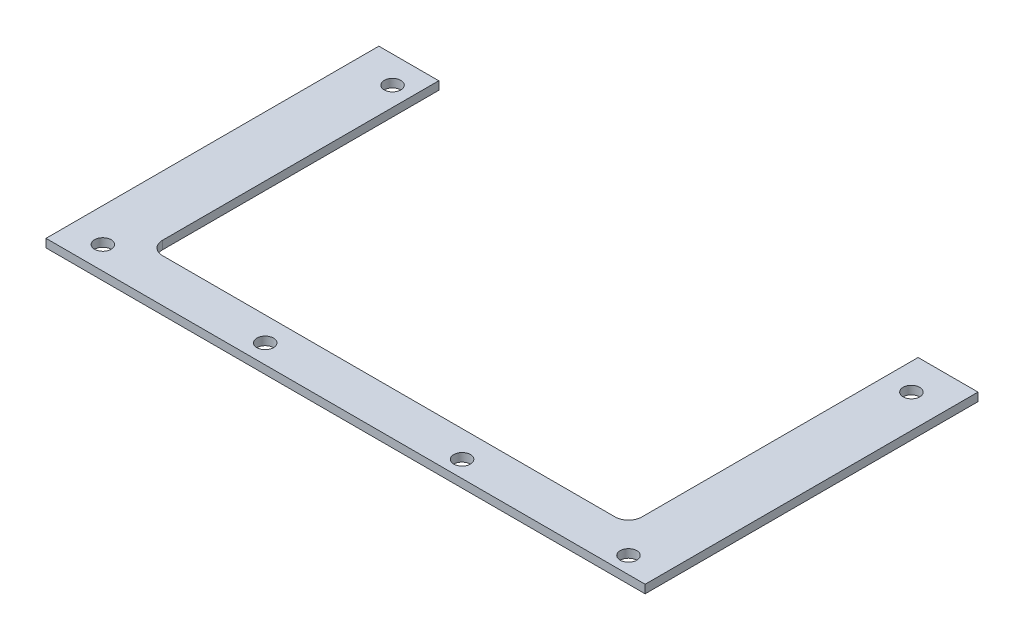
SolidWorks part; units mm, degrees
ref_plane "Front Plane" through (0, 0, 0) normal (0, 0, 1) x (1, 0, 0)
ref_plane "Top Plane" through (0, 0, 0) normal (0, 1, 0) x (1, 0, 0)
ref_plane "Right Plane" through (0, 0, 0) normal (1, 0, 0) x (0, 0, -1)
sketch "Sketch1" plane through (0, 25.4, 0) normal (0, 1, 0) x (1, 0, 0)
  line L0 (-86.36, 311.15) -> (86.36, 311.15)
  line L1 (-101.6, 342.9) -> (101.6, 342.9)
  line L2 (-101.6, 342.9) -> (-101.6, 215.9)
  line L3 (-101.6, 215.9) -> (101.6, 215.9)
  line L4 (101.6, 342.9) -> (101.6, 215.9)
  line L5 (-86.36, 234.95) -> (86.36, 234.95)
  line L6 (-88.9, 237.49) -> (-88.9, 308.61)
  line L7 (88.9, 308.61) -> (88.9, 237.49)
  line L8 (88.9, 308.61) -> (88.9, 237.49)
  line L9 (-88.9, 237.49) -> (-88.9, 308.61)
  line L10 (-86.36, 234.95) -> (86.36, 234.95)
  line L11 (-86.36, 311.15) -> (86.36, 311.15)
  line L13 (91.44, 342.9) -> (91.44, 237.49)
  line L14 (-86.36, 232.41) -> (86.36, 232.41)
  line L15 (-91.44, 237.49) -> (-91.44, 342.9)
  line L16 (-86.36, 313.69) -> (86.36, 313.69)
  line L17 (91.44, 308.61) -> (91.44, 237.49) construction
  line L18 (-91.44, 237.49) -> (-91.44, 308.61) construction
  line L20 (101.6, 215.9) -> (114.3, 215.9)
  line L21 (101.6, 215.9) -> (101.6, 342.9)
  line L22 (101.6, 342.9) -> (114.3, 342.9)
  line L23 (114.3, 215.9) -> (114.3, 342.9)
  line L24 (-114.3, 215.9) -> (-101.6, 215.9)
  line L25 (-114.3, 215.9) -> (-114.3, 342.9)
  line L26 (-114.3, 342.9) -> (-101.6, 342.9)
  line L27 (-101.6, 215.9) -> (-101.6, 342.9)
  arc A2 (98.425, 215.9) -> (104.775, 215.9) centre (101.6, 215.9) ccw construction
  arc A3 (98.425, 215.9) -> (104.775, 215.9) centre (101.6, 215.9) ccw
  arc A4 (-88.9, 237.49) -> (-86.36, 234.95) centre (-86.36, 237.49) ccw
  arc A5 (88.9, 308.61) -> (86.36, 311.15) centre (86.36, 308.61) ccw
  arc A6 (-86.36, 311.15) -> (-88.9, 308.61) centre (-86.36, 308.61) ccw
  arc A7 (86.36, 234.95) -> (88.9, 237.49) centre (86.36, 237.49) ccw
  arc A8 (86.36, 234.95) -> (88.9, 237.49) centre (86.36, 237.49) ccw
  arc A9 (-86.36, 311.15) -> (-88.9, 308.61) centre (-86.36, 308.61) ccw
  arc A10 (88.9, 308.61) -> (86.36, 311.15) centre (86.36, 308.61) ccw
  arc A11 (-88.9, 237.49) -> (-86.36, 234.95) centre (-86.36, 237.49) ccw
  arc A12 (86.36, 232.41) -> (91.44, 237.49) centre (86.36, 237.49) ccw
  arc A13 (-91.44, 237.49) -> (-86.36, 232.41) centre (-86.36, 237.49) ccw
  arc A14 (-86.36, 313.69) -> (-91.44, 308.61) centre (-86.36, 308.61) ccw
  arc A15 (91.44, 308.61) -> (86.36, 313.69) centre (86.36, 308.61) ccw
  arc A16 (114.3, 339.725) -> (117.475, 342.9) centre (114.3, 342.9) ccw construction
  arc A17 (114.3, 339.725) -> (117.475, 342.9) centre (114.3, 342.9) ccw
  arc A18 (-114.3, 219.075) -> (-111.125, 215.9) centre (-114.3, 215.9) ccw construction
  arc A19 (-114.3, 219.075) -> (-111.125, 215.9) centre (-114.3, 215.9) ccw
  dimension "D1" = 2.54
extrude "Boss-Extrude1" add sketch "Sketch1" along normal blind 3.175 contours A13 L15 L1 L2 L3 L4 L13 A12 L14 | L26 L25 L24 L2 | L20 L23 L22 L4
hole_wizard "1/4 (0.25) Diameter Hole1" positions "Sketch5" profile "Sketch6" hole size "1/4" standard "ANSI Inch" end condition through all
sketch "Sketch5" plane through (0, 28.575, 0) normal (0, 1, 0) x (1, 0, 0)
  line L0 (88.9, 330.2) -> (114.3, 330.2)
  line L2 (6.35, 215.9) -> (6.35, 370.9858) construction
  line L3 (9.525, 215.9) -> (3.175, 215.9) construction
  line L5 (127, 215.9) -> (127, 228.6)
  line L7 (127, 222.25) -> (-8.2455, 222.25) construction
  line L8 (38.1, 215.9) -> (38.1, 228.6)
  line L10 (101.6, 222.25) -> (101.6, 330.2)
  line L11 (0, 215.9) -> (1.8498, 368.6609) construction
  line L12 (-114.3, 215.9) -> (114.3, 215.9) construction
  arc A0 (114.3, 327.025) -> (114.3, 333.375) centre (114.3, 330.2) ccw construction
  arc A1 (90.9687, 330.2762) -> (86.8313, 330.2762) centre (88.9, 330.2) ccw construction
  arc A2 (90.9687, 330.2762) -> (86.8313, 330.2762) centre (88.9, 330.2) ccw
  arc A3 (114.3, 327.025) -> (114.3, 333.375) centre (114.3, 330.2) ccw
  circle A4 centre (127, 228.6) radius 3.175 construction
  circle A5 centre (127, 215.9) radius 3.175 construction
  circle A6 centre (127, 228.6) radius 3.175
  circle A7 centre (127, 215.9) radius 3.175
  arc A8 (34.925, 215.9) -> (41.275, 215.9) centre (38.1, 215.9) ccw construction
  arc A9 (34.925, 215.9) -> (41.275, 215.9) centre (38.1, 215.9) ccw
  point P0 (101.6, 330.2)
  point P36 (101.6, 222.25)
  point P39 (38.1, 222.25)
  point P63 (-98.8025, 332.6267)
  point P64 (-101.4164, 224.7084)
  point P65 (-37.9351, 223.1707)
sketch "Sketch6" plane through (101.6, 28.575, -330.2) normal (1, 0, 0) x (0, 0, 1)
  line L0 (0, 0) -> (0, 3.175)
  line L1 (0, 3.175) -> (3.175, 3.175)
  line L2 (3.175, 3.175) -> (3.175, 0)
  line L5 (3.175, 0) -> (0, 0)
  line L11 (0, -6.35) -> (0, 107.95) construction
  dimension "Thru Hole Dia." = 6.35
  dimension "Thru Hole Depth" = 3.175
